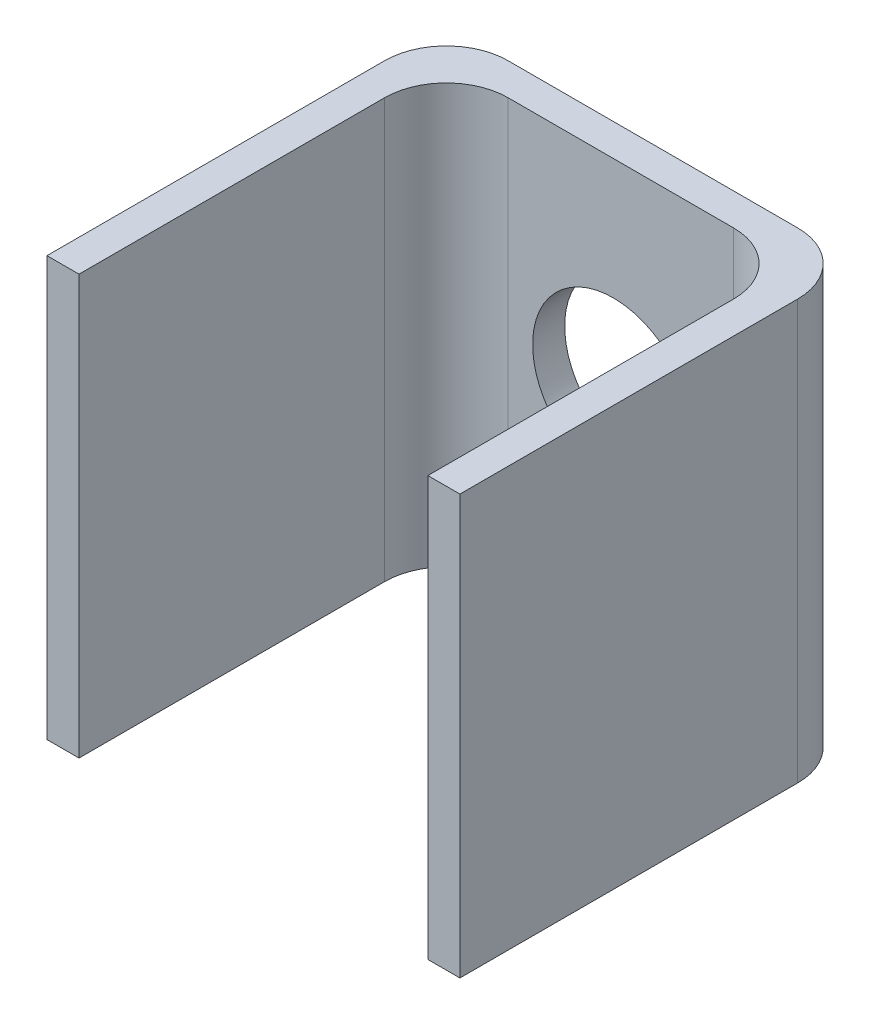
SolidWorks part; units mm, degrees
ref_plane "Front Plane" through (0, 0, 0) normal (0, 0, 1) x (1, 0, 0)
ref_plane "Top Plane" through (0, 0, 0) normal (0, 1, 0) x (1, 0, 0)
ref_plane "Right Plane" through (0, 0, 0) normal (1, 0, 0) x (0, 0, -1)
ref_plane "Plane1" through (0, 11.3855, 0) normal (0, 1, 0) x (-1, 0, 0)
sketch "Sketch1" plane through (0, 11.3855, 0) normal (0, 1, 0) x (-1, 0, 0)
  line L0 (5.7493, 0) -> (11.7183, 0)
  line L1 (12.9883, 1.27) -> (12.9883, 8.2296)
  line L2 (12.9883, 8.2296) -> (12.3279, 8.2296)
  line L3 (12.3279, 8.2296) -> (12.3279, 1.9304)
  line L4 (11.0579, 0.6604) -> (6.4097, 0.6604)
  line L5 (5.1397, 1.9304) -> (5.1397, 8.2296)
  line L6 (5.1397, 8.2296) -> (4.4793, 8.2296)
  line L7 (4.4793, 8.2296) -> (4.4793, 1.27)
  arc A0 (4.4793, 1.27) -> (5.7493, 0) centre (5.7493, 1.27) ccw
  arc A1 (11.7183, 0) -> (12.9883, 1.27) centre (11.7183, 1.27) ccw
  arc A2 (12.3279, 1.9304) -> (11.0579, 0.6604) centre (11.0579, 1.9304) cw
  arc A3 (6.4097, 0.6604) -> (5.1397, 1.9304) centre (6.4097, 1.9304) cw
extrude "Boss-Extrude1" add sketch "Sketch1" against normal blind 8.636
hole_wizard "Hole1" positions "Sketch3" profile "Sketch2" legacy
sketch "Sketch3" plane through (0, 0, 0.6604) normal (0, 0, 1) x (1, 0, 0)
  point P0 (-8.8865, 7.2342)
sketch "Sketch2" plane through (-8.8865, 7.2342, 0.6604) normal (1, 0, 0) x (0, -1, 0)
  line L0 (0, 0) -> (0, 0.6604)
  line L1 (0, 0.6604) -> (1.6637, 0.6604)
  line L2 (1.6637, 0.6604) -> (1.6637, 0)
  line L3 (1.6637, 0) -> (0, 0)
  line L4 (0, 110) -> (0, -10) construction
  dimension "Diameter" = 3.3274
  dimension "Depth" = 0.6604
